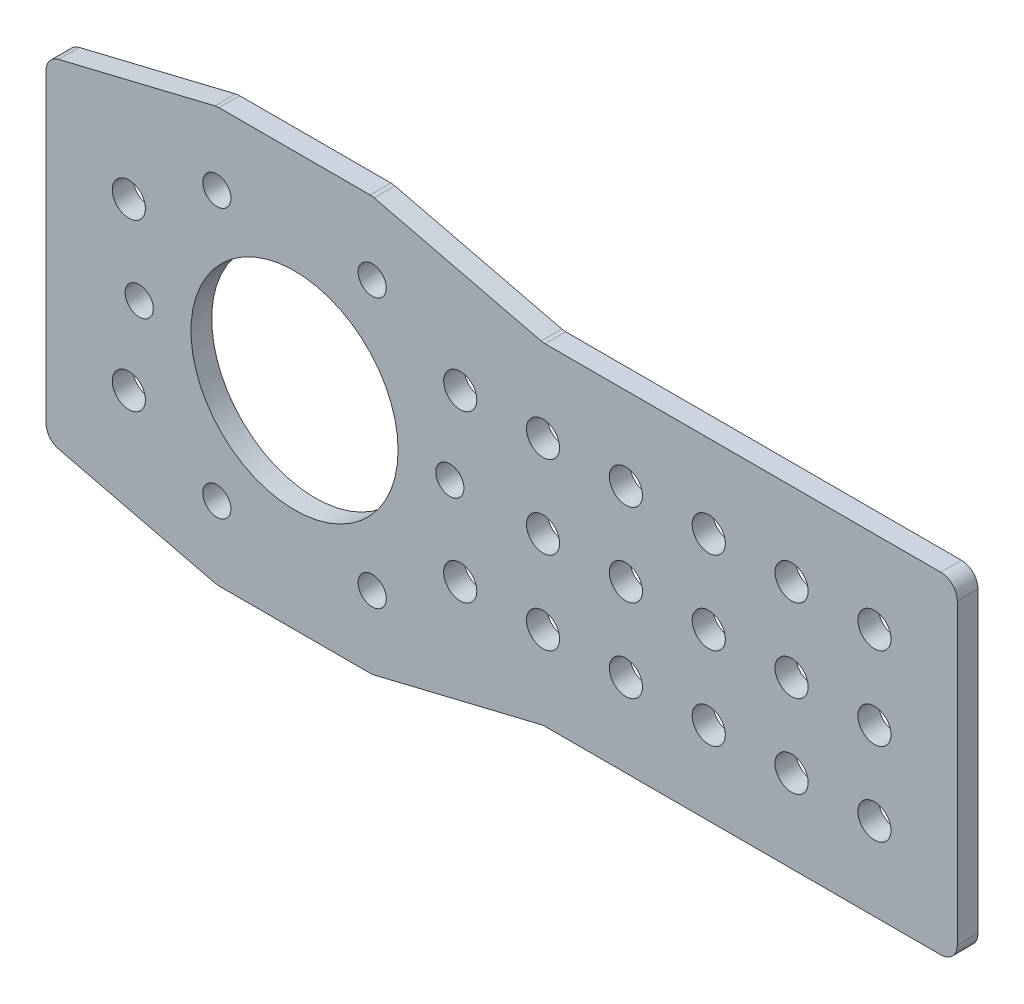
SolidWorks part; units mm, degrees
ref_plane "Front Plane" through (0, 0, 0) normal (0, 0, 1) x (1, 0, 0)
ref_plane "Top Plane" through (0, 0, 0) normal (0, 1, 0) x (1, 0, 0)
ref_plane "Right Plane" through (0, 0, 0) normal (1, 0, 0) x (0, 0, -1)
sketch "Sketch1" plane through (0, 0, 0) normal (0, 0, 1) x (1, 0, 0)
  arc A19 (-480.6, -14.2) -> (-459.2, -14.2) centre (-469.9, 0) ccw
  arc A20 (-446.9968, 12.573) -> (-442.0032, 12.573) centre (-444.5, 12.7) ccw
  arc A21 (-421.5968, 12.573) -> (-416.6032, 12.573) centre (-419.1, 12.7) ccw
  arc A22 (-434.2968, 12.573) -> (-429.3032, 12.573) centre (-431.8, 12.7) ccw
  arc A23 (-434.2968, -0.127) -> (-429.3032, -0.127) centre (-431.8, 0) ccw
  arc A24 (-421.5968, -0.127) -> (-416.6032, -0.127) centre (-419.1, 0) ccw
  arc A25 (-421.5968, -12.827) -> (-416.6032, -12.827) centre (-419.1, -12.7) ccw
  arc A26 (-434.2968, -12.827) -> (-429.3032, -12.827) centre (-431.8, -12.7) ccw
  arc A27 (-446.9968, -12.827) -> (-442.0032, -12.827) centre (-444.5, -12.7) ccw
  arc A28 (-491.5572, 0.127) -> (-494.0059, 2.139) centre (-493.7125, 0) ccw
  arc A29 (-494.0059, -2.139) -> (-491.5572, -0.127) centre (-493.7125, 0) ccw
  arc A30 (-497.7968, 12.573) -> (-492.8032, 12.573) centre (-495.3, 12.7) ccw
  arc A31 (-497.7968, -12.827) -> (-492.8032, -12.827) centre (-495.3, -12.7) ccw
  circle A32 centre (-481.8062, -20.6222) radius 2.159
  circle A33 centre (-457.9938, -20.6222) radius 2.159
  arc A34 (-448.2428, -0.127) -> (-445.7941, -2.139) centre (-446.0875, 0) ccw
  arc A35 (-445.7941, 2.139) -> (-448.2428, 0.127) centre (-446.0875, 0) ccw
  circle A36 centre (-457.9937, 20.6222) radius 2.159
  circle A37 centre (-481.8063, 20.6222) radius 2.159
sketch "Sketch2" plane through (0, 0, 0) normal (0, 0, 1) x (1, 0, 0)
  line L0 (-508, 25.4) -> (-481.8062, 31.75)
  line L1 (-481.8062, 31.75) -> (-457.9937, 31.75)
  line L2 (-457.9937, 31.75) -> (-431.8, 25.4)
  line L3 (-431.8, 25.4) -> (-368.3, 25.4)
  line L4 (-368.3, 25.4) -> (-368.3, -25.4)
  line L5 (-368.3, -25.4) -> (-431.8, -25.4)
  line L6 (-431.8, -25.4) -> (-457.9937, -31.75)
  line L7 (-457.9937, -31.75) -> (-481.8062, -31.75)
  line L8 (-481.8062, -31.75) -> (-508, -25.4)
  line L9 (-508, 25.4) -> (-508, -25.4)
  line L10 (-419.1, 12.7) -> (-406.4, 12.7) construction
  circle A0 centre (-469.9, 0) radius 15.875
  circle A1 centre (-457.9937, 20.6222) radius 2.159
  circle A2 centre (-481.8063, 20.6222) radius 2.159
  circle A3 centre (-493.7125, 0) radius 2.159
  circle A4 centre (-481.8062, -20.6222) radius 2.159
  circle A5 centre (-457.9938, -20.6222) radius 2.159
  circle A6 centre (-446.0875, 0) radius 2.159
  circle A7 centre (-495.3, 12.7) radius 2.54
  circle A8 centre (-495.3, -12.7) radius 2.54
  circle A9 centre (-444.5, -12.7) radius 2.54
  circle A10 centre (-431.8, -12.7) radius 2.54
  circle A11 centre (-419.1, -12.7) radius 2.54
  circle A12 centre (-419.1, 0) radius 2.54
  circle A13 centre (-431.8, 0) radius 2.54
  circle A14 centre (-431.8, 12.7) radius 2.54
  circle A15 centre (-419.1, 12.7) radius 2.54
  circle A16 centre (-444.5, 12.7) radius 2.54
  circle A17 centre (-406.4, 12.7) radius 2.54
  circle A18 centre (-406.4, 0) radius 2.54
  circle A19 centre (-406.4, -12.7) radius 2.54
  circle A20 centre (-393.7, 12.7) radius 2.54
  circle A21 centre (-393.7, 0) radius 2.54
  circle A22 centre (-393.7, -12.7) radius 2.54
  circle A23 centre (-381, 12.7) radius 2.54
  circle A24 centre (-381, 0) radius 2.54
  circle A25 centre (-381, -12.7) radius 2.54
  point P64 (-447.4508, 31.75)
  point P82 (-431.8, 25.4)
  point P83 (-457.9937, 31.75)
  point P84 (0, 0)
  dimension "D1" = 4.318
  dimension "D2" = 31.75
  dimension "D3" = 5.08
  dimension "D4" = 50.8
  dimension "D5" = 25.4
  dimension "D6" = 63.5
  dimension "D7" = 6.35
  dimension "D8" = 38.1
  dimension "D9" = 38.1
  dimension "D11" = 12.7
  dimension "D12" = 101.6
  dimension "D13" = 50.8
  dimension "D10" = 4
extrude "Boss-Extrude1" add sketch "Sketch2" along normal blind 3.175
fillet "Fillet1" radius 2.54 10 edges at (-431.8, -25.4, 1.5875) (-457.9937, -31.75, 1.5875) (-481.8062, -31.75, 1.5875) (-481.8062, 31.75, 1.5875) (-457.9937, 31.75, 1.5875) (-431.8, 25.4, 1.5875) (-508, -25.4, 1.5875) (-508, 25.4, 1.5875) (-368.3, -25.4, 1.5875) (-368.3, 25.4, 1.5875)
